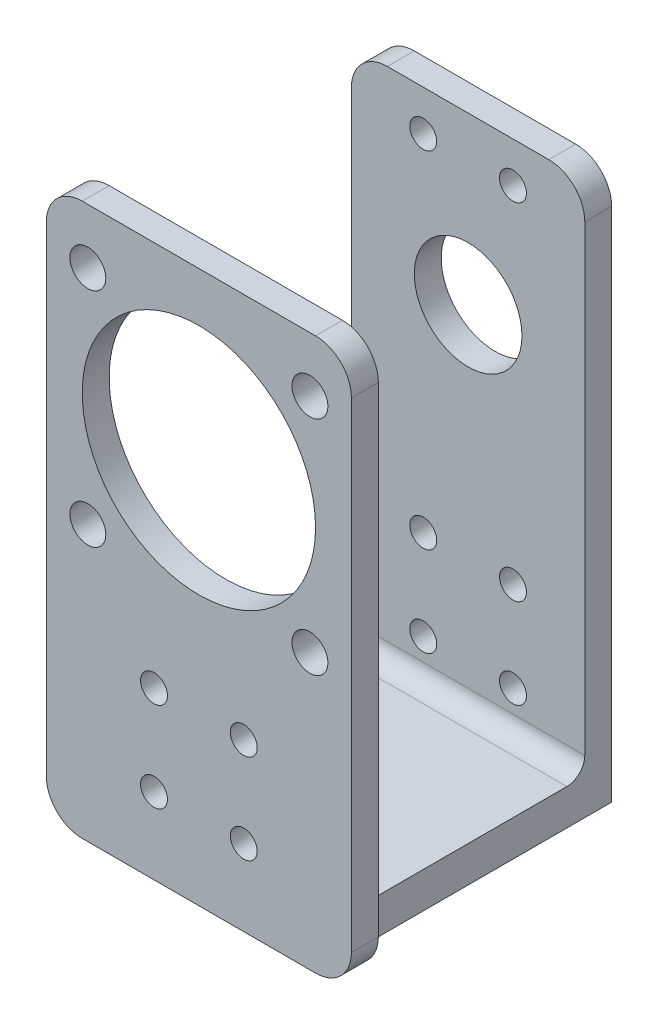
SolidWorks part; units mm, degrees
material "1060 合金"
ref_plane "Front" through (0, 0, 0) normal (0, 0, 1) x (1, 0, 0)
ref_plane "Top" through (0, 0, 0) normal (0, 1, 0) x (1, 0, 0)
ref_plane "Right" through (0, 0, 0) normal (1, 0, 0) x (0, 0, -1)
sketch "草图1" plane through (0, 0, 0) normal (0, 0, 1) x (1, 0, 0)
  line L1 (-13, 28.75) -> (13, 28.75)
  line L2 (-13, 28.75) -> (-13, -28.75)
  line L3 (-13, -28.75) -> (13, -28.75)
  line L4 (13, 28.75) -> (13, -28.75)
  line L5 (-13, 28.75) -> (13, -28.75) construction
  line L6 (-13, -28.75) -> (13, 28.75) construction
  line L7 (-5, 24.25) -> (5, 24.25) construction
  line L8 (-5, 24.25) -> (-5, -24.25) construction
  line L9 (-5, -24.25) -> (5, -24.25) construction
  line L10 (5, 24.25) -> (5, -24.25) construction
  line L11 (-5, 24.25) -> (5, -24.25) construction
  line L12 (-5, -24.25) -> (5, 24.25) construction
  circle A0 centre (-5, 24.25) radius 1.5
  circle A1 centre (5, 24.25) radius 1.5
  circle A2 centre (5, -24.25) radius 1.5
  circle A3 centre (-5, -24.25) radius 1.5
  circle A4 centre (0, 10.25) radius 6
  point P0 (0, 0)
  point P5 (0, 0)
  dimension "D5" = 3
  dimension "D6" = 3
  dimension "D7" = 3
  dimension "D8" = 3
  dimension "D9" = 12
  dimension "D10" = 14
  dimension "D11" = 13
  dimension "D1" = 57.5
  dimension "D2" = 26
  dimension "D3" = 48.5
  dimension "D4" = 10
extrude "凸台-拉伸1" add sketch "草图1" along normal blind 3
sketch "草图2" plane through (0, 0, 0) normal (0, 0, -1) x (-1, 0, 0)
  line L1 (13, -28.75) -> (-13, -28.75)
  line L2 (13, -28.75) -> (13, -31.75)
  line L3 (13, -31.75) -> (-13, -31.75)
  line L4 (-13, -28.75) -> (-13, -31.75)
  dimension "D1" = 3
  dimension "D2" = 26
extrude "凸台-拉伸2" add sketch "草图2" against normal blind 33
sketch "草图3" plane through (0, 0, 33) normal (0, 0, 1) x (1, 0, 0)
  line L0 (13, -28.75) -> (13, 28.75) construction
  line L1 (-17, -31.75) -> (17, -31.75)
  line L2 (-17, -31.75) -> (-17, 28.75)
  line L3 (-17, 28.75) -> (17, 28.75)
  line L4 (17, -31.75) -> (17, 28.75)
  line L6 (0, 27.75) -> (0, 10.25) construction
  line L7 (0, 10.25) -> (12.3744, 22.6244) construction
  line L8 (13, -31.75) -> (-13, -31.75) construction
  circle A0 centre (0, 10.25) radius 17.5 construction
  circle A1 centre (12.3744, 22.6244) radius 2
  circle A2 centre (12.3744, -2.1244) radius 2
  circle A3 centre (-12.3744, -2.1244) radius 2
  circle A4 centre (-12.3744, 22.6244) radius 2
  circle A5 centre (0, 10.25) radius 13
  point P23 (0, 10.25)
  dimension "D5" = 35
  dimension "D7" = 4
  dimension "D9" = 26
  dimension "D1" = 60.5
  dimension "D2" = 34
  dimension "D3" = 4
  dimension "D4" = 0
  dimension "D6" = 45
  dimension "D8" = 4
extrude "凸台-拉伸3" add sketch "草图3" against normal blind 3
fillet "圆角1" radius 2 2 edges at (0, -28.75, 30) (0, -28.75, 3)
sketch "草图4" plane through (0, -31.75, 0) normal (0, -1, 0) x (1, 0, 0)
  line L8 (13, 0) -> (13, 30)
  line L9 (13, 30) -> (17, 30)
  line L10 (17, 30) -> (17, 33)
  line L11 (17, 33) -> (-17, 33)
  line L12 (-17, 33) -> (-17, 30)
  line L13 (-17, 30) -> (-13, 30)
  line L14 (-13, 30) -> (-13, 0)
  line L15 (-13, 0) -> (13, 0)
  line L16 (13, 0) -> (13, 30)
  line L17 (13, 30) -> (17, 30)
  line L18 (17, 30) -> (17, 33)
  line L19 (17, 33) -> (-17, 33)
  line L20 (-17, 33) -> (-17, 30)
  line L21 (-17, 30) -> (-13, 30)
  line L22 (-13, 30) -> (-13, 0)
  line L23 (-13, 0) -> (13, 0)
  dimension "D1" = 0
extrude "凸台-拉伸4" add sketch "草图4" along normal blind 1
fillet "圆角2" radius 4 6 edges at (-13, 28.75, 1.5) (13, 28.75, 1.5) (-17, 28.75, 31.5) (17, 28.75, 31.5) (17, -32.75, 31.5) (-17, -32.75, 31.5)
sketch "草图5" plane through (0, 0, 0) normal (0, 0, -1) x (-1, 0, 0)
  line L0 (13, 24.75) -> (13, -32.75) construction
  line L1 (-13, -32.75) -> (-13, 24.75) construction
  circle A0 centre (-5, -24.25) radius 1.5
  circle A1 centre (5, -24.25) radius 1.5
  circle A2 centre (0, 10.25) radius 21 construction
  circle A3 centre (-5, -14.2449) radius 1.5
  circle A4 centre (5, -14.2449) radius 1.5
  dimension "D1" = 3
  dimension "D2" = 3
  dimension "D3" = 42
  dimension "D4" = 3
  dimension "D5" = 3
  dimension "D6" = 25
  dimension "D7" = 25
  dimension "D8" = 8
  dimension "D9" = 8
extrude "切除-拉伸1" cut sketch "草图5" against normal through all
